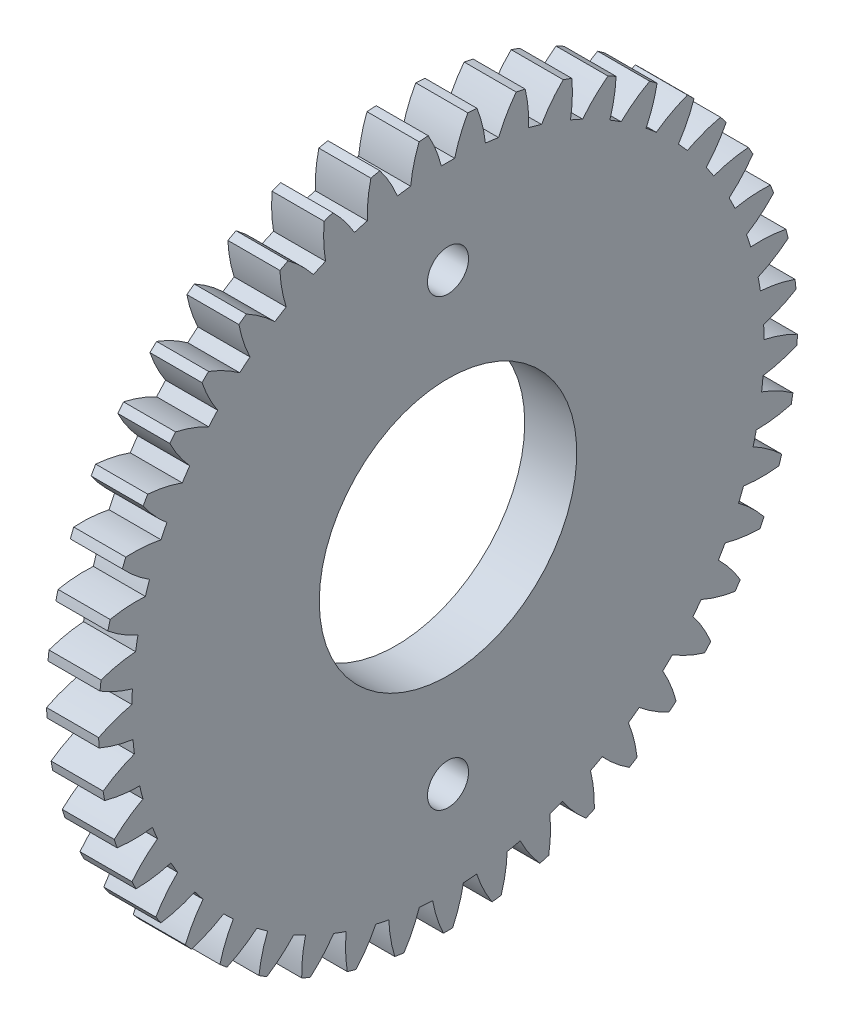
SolidWorks part; units mm, degrees
material "Cedar"
ref_plane "Plane1" through (0, 0, 0) normal (0, 0, 1) x (1, 0, 0)
ref_plane "Plane2" through (0, 0, 0) normal (0, 1, 0) x (1, 0, 0)
ref_plane "Plane3" through (0, 0, 0) normal (1, 0, 0) x (0, 0, -1)
sketch "HoldingSke" plane through (0, 0, 0) normal (0, 1, 0) x (1, 0, 0)
  line L0 (0, 0) -> (359.2102, -359.2102)
  line L1 (-15, 0) -> (100, 0) construction
  line L2 (0, 0) -> (-2.1039, 2.3779)
  line L3 (0, 0) -> (-11.863, 4.5341)
  line L4 (0, 0) -> (6.1066, 6.1066)
  line L5 (0, 0) -> (-47.5972, -17.7524)
  line L6 (0, 0) -> (-3.6847, -2.4861)
  line L7 (-2.1039, 2.3779) -> (8.8308, 51.9871)
  line L8 (-76.2, 54.61) -> (-69.596, 54.61)
  line L9 (-71.009, 38.7566) -> (-53.1078, 45.2721)
  line L10 (-76.2, 71.12) -> (104.1128, 71.12)
  line L11 (0, 0) -> (-4.445, 0)
  line L12 (-76.2, 101.6) -> (-76.1492, 101.6)
  line L13 (24.9733, 27.94) -> (52.9518, 28.4284)
  line L14 (24.9733, 27.94) -> (25.0241, 27.9398)
  line L15 (24.9733, 27.94) -> (100.4021, 29.52)
  circle A0 centre (0, 0) radius 3.175
  circle A1 centre (0, 0) radius 27.0002
  circle A2 centre (0, 0) radius 38.1
  circle A3 centre (0, 0) radius 3.175
  dimension "MHD" = 54.0004
  dimension "Hub_dia" = 76.2
  dimension "Bore" = 6.35
  dimension "MBD" = 6.35
  dimension "Num_teeth" = 45
  dimension "Pitch_radius" = 180.3128
  dimension "Pitch" = 508
  dimension "Width" = 4.445
  dimension "Overall_len" = 50.8
  dimension "Show_teeth" = 45
  dimension "Thickness" = 4.445
  dimension "OAL" = 50.8001
  dimension "T_dim" = 6.604
  dimension "Ap" = 20
  dimension "H" = 19.05
  dimension "Backlash" = 0.0508
  dimension "Addendum_fac" = 1
  dimension "Dedendum_fac" = 1.2
  dimension "Clearance_fac" = 0.2
  dimension "Dedendum_add" = 0.0508
sketch "BasProSke" plane through (0, 0, 0) normal (0, 1, 0) x (1, 0, 0)
  line L0 (-10, 0) -> (60, 0) construction
  line L1 (0, 0) -> (0, 29.845)
  line L2 (0, 0) -> (4.445, 0)
  line L3 (4.445, 0) -> (4.445, 29.845)
  line L4 (4.445, 29.845) -> (0, 29.845)
  dimension "Diameter" = 59.69
  dimension "Thickness" = 4.445
revolve "Base-Revolve" add sketch "BasProSke" angle 360 about L0
sketch "TooCutSke" plane through (0, 0, 0) normal (1, 0, 0) x (0, 0, -1)
  line L1 (0, 0) -> (0, 107) construction
  line L2 (0, 0) -> (-1.0861, 28.5544) construction
  line L3 (0, 0) -> (-3.9846, 56.982) construction
  line L4 (-1.0861, 28.5544) -> (-1.9923, 28.491) construction
  arc A0 (0.5698, 26.9942) -> (-0.5698, 26.9942) centre (0, 0) ccw
  arc A1 (1.7035, 29.8218) -> (-1.7035, 29.8218) centre (0, 0) ccw
  circle A2 centre (0, 0) radius 28.575 construction
  circle A3 centre (0, 0) radius 26.8517 construction
  arc A4 (-0.5698, 26.9942) -> (-1.7035, 29.8218) centre (-11.6511, 24.1923) ccw
  arc A5 (1.7035, 29.8218) -> (0.5698, 26.9942) centre (11.6511, 24.1923) ccw
  dimension "Root_dia" = 54.0004
  dimension "Overcut_dia" = 59.7408
  dimension "Pitch_dia" = 57.15
  dimension "Base_dia" = 53.7034
  dimension "Flank_rad" = 11.43
  dimension "Half_ang" = 4
  dimension "Half_CT" = 0.9084
extrude "ToothCut" cut sketch "TooCutSke" along normal through all
fillet "Breaks" [suppressed] radius 0.0254
fillet "RootFillets" [suppressed] radius 0.3048
pattern_circular "TeethCuts" count 45 over 360 about axis through (0, 0, 0) along (1, 0, 0) of "ToothCut", "RootFillets", "Breaks"
sketch "HubNeaOneSke" plane through (0, 0, 0) normal (-1, 0, 0) x (0, 0, 1)
  circle A0 centre (0, 0) radius 27.0002
  dimension "Diameter" = 54.0004
extrude "HubNearOne" [suppressed] add sketch "HubNeaOneSke" along normal blind 46.3551
sketch "HubNeaBotSke" plane through (0, 0, 0) normal (-1, 0, 0) x (0, 0, 1)
  circle A0 centre (0, 0) radius 27.0002
  dimension "Diameter" = 54.0004
extrude "HubNearBoth" [suppressed] add sketch "HubNeaBotSke" along normal blind 23.1775
ref_plane "FarPln" through (4.445, 0, 0) normal (1, 0, 0) x (0, 0, -1)
sketch "HubFarSke" plane through (4.445, 0, 0) normal (1, 0, 0) x (0, 0, -1)
  circle A0 centre (0, 0) radius 27.0002
  dimension "Diameter" = 54.0004
extrude "HubFar" [suppressed] add sketch "HubFarSke" along normal blind 23.1775
sketch "BorSke" plane through (0, 0, 0) normal (1, 0, 0) x (0, 0, -1)
  circle A0 centre (0, 0) radius 10.9982
  dimension "Diameter" = 21.9964
extrude "Bore" cut sketch "BorSke" along normal mid plane 101.6001
sketch "KeySke" plane through (0, 0, 0) normal (1, 0, 0) x (0, 0, -1)
  line L0 (-0.127, 0) -> (-0.127, 3.429)
  line L1 (-0.127, 3.429) -> (0.127, 3.429)
  line L2 (0.127, 3.429) -> (0.127, 0)
  line L3 (0, 0) -> (0, 34) construction
  line L4 (-0.127, 0) -> (0.127, 0)
  dimension "Offset" = 3.429
  dimension "Width" = 0.254
extrude "Keyway" [suppressed] cut sketch "KeySke" along normal mid plane 101.6001
pattern_circular "Keyway2" [suppressed] count 2 every 90 about axis through (-10, 0, 0) along (1, 0, 0)
sketch "Sketch1" plane through (0, 0, 0) normal (-1, 0, 0) x (0, 0, 1)
  circle A0 centre (0, 18.9992) radius 1.7526
  circle A1 centre (0, -18.9992) radius 1.7526
  point P2 (0, 0)
  dimension "D1" = 3.5052
  dimension "D3" = 3.5052
  dimension "D2" = 18.9992
  dimension "D4" = 18.9992
extrude "Cut-Extrude1" cut sketch "Sketch1" against normal through all
equation "' \"Pitch@HoldingSke\" = 4"
equation "' \"Num_teeth@HoldingSke\" = 12"
equation "' \"Ap@HoldingSke\" =  20"
equation "' \"Width@HoldingSke\" = 0.5"
equation "' \"Hub_dia@HoldingSke\"= 1"
equation "' \"Overall_len@HoldingSke\" = 1.0"
equation "' \"Bore@HoldingSke\" = 0.75"
equation "' \"T_dim@HoldingSke\" = 0.85"
equation "' \"Width@KeySke\" = 0.25"
equation "' \"Show_teeth@HoldingSke\" = 13"
equation "' \"Backlash@HoldingSke\" = 0.009"
equation "' \"Addendum_fac@HoldingSke\" = 1.0"
equation "' \"Dedendum_fac@HoldingSke\" = 1.25"
equation "' \"Dedendum_add@HoldingSke\" = 0.00005"
equation "' \"Clearance_fac@HoldingSke\" = 0.25"
equation "' \"Pitch@HoldingSke\" = 0.5"
equation "' \"Num_teeth@HoldingSke\" = 23"
equation "' \"Show_teeth@HoldingSke\" = 23"
equation "' \"Backlash@HoldingSke\" = 0.0375"
equation "\"Overcut_dia@TooCutSke\" = (\"Num_teeth@HoldingSke\" + 2 * \"Addendum_fac@HoldingSke\") / \"Pitch@HoldingSke\" + 0.002"
equation "\"Pitch_dia@TooCutSke\" = \"Num_teeth@HoldingSke\" / \"Pitch@HoldingSke\""
equation "\"Base_dia@TooCutSke\" = \"Num_teeth@HoldingSke\" / \"Pitch@HoldingSke\" * cos((\"Ap@HoldingSke\"  * 3.14159265 / 180))"
equation "\"Root_dia@TooCutSke\" = (\"Num_teeth@HoldingSke\" + 2) / \"Pitch@HoldingSke\" - 2 * (\"Addendum_fac@HoldingSke\" + \"Dedendum_fac@HoldingSke\") / \"Pitch@HoldingSke\" - \"Dedendum_add@HoldingSke\" * 2"
equation "\"Half_ang@TooCutSke\" = 180 / \"Num_teeth@HoldingSke\""
equation "\"Half_CT@TooCutSke\" = \"Num_teeth@HoldingSke\" / \"Pitch@HoldingSke\" * sin((3.14159265 / 2 / \"Num_teeth@HoldingSke\")) / 2 - 7 * \"Backlash@HoldingSke\" / 4"
equation "\"Flank_rad@TooCutSke\" = \"Num_teeth@HoldingSke\" / \"Pitch@HoldingSke\" / 5"
equation "\"Radius@RootFillets\" = \"Clearance_fac@HoldingSke\" / \"Pitch@HoldingSke\" + \"Dedendum_add@HoldingSke\""
equation "\"Break_rad@Breaks\" = 0.02 / \"Pitch@HoldingSke\""
equation "\"Thickness@HoldingSke\" = \"Width@HoldingSke\""
equation "\"OAL@HoldingSke\" = \"Thickness@HoldingSke\""
equation "\"MHD@HoldingSke\" = (\"Num_teeth@HoldingSke\" + 2) / \"Pitch@HoldingSke\" - 2 * (\"Addendum_fac@HoldingSke\" + \"Dedendum_fac@HoldingSke\")  / \"Pitch@HoldingSke\" - \"Dedendum_add@HoldingSke\" * 2"
equation "\"MBD@HoldingSke\" = (\"Num_teeth@HoldingSke\" + 2) / \"Pitch@HoldingSke\" - 2 * (\"Addendum_fac@HoldingSke\" + \"Dedendum_fac@HoldingSke\")  / \"Pitch@HoldingSke\" - \"Dedendum_add@HoldingSke\" * 2 - 0.002"
equation "\"MHD@HoldingSke\" = ((sgn( \"MHD@HoldingSke\" - \"Hub_dia@HoldingSke\" )-1)*( \"MHD@HoldingSke\" - \"Hub_dia@HoldingSke\" ))/-2+ \"Hub_dia@HoldingSke\""
equation "\"MBD@HoldingSke\" = ((sgn( \"MBD@HoldingSke\" - \"Bore@HoldingSke\" )-1)*( \"MBD@HoldingSke\" - \"Bore@HoldingSke\" ))/-2+ \"Bore@HoldingSke\""
equation "\"OAL@HoldingSke\" = ((sgn( \"OAL@HoldingSke\" - \"Overall_len@HoldingSke\" )+1)*( \"OAL@HoldingSke\" - \"Overall_len@HoldingSke\" ))/2 + \"Overall_len@HoldingSke\" + 0.000002"
equation "\"Num_teeth@TeethCuts\" = int( \"Show_teeth@HoldingSke\" ) + 1"
equation "\"Num_teeth@TeethCuts\" = ((sgn( \"Num_teeth@TeethCuts\" - \"Num_teeth@HoldingSke\" )-1)*( \"Num_teeth@TeethCuts\" - \"Num_teeth@HoldingSke\" ))/-2+ \"Num_teeth@HoldingSke\""
equation "\"Num_teeth@TeethCuts\" = ((sgn( \"Num_teeth@TeethCuts\" - 2.0)+1)*( \"Num_teeth@TeethCuts\" - 2.0))/2 +2.0"
equation "\"Angle@TeethCuts\" = 360.0 / \"Num_teeth@HoldingSke\""
equation "\"Diameter@BasProSke\" = (\"Num_teeth@HoldingSke\" + 2 * \"Addendum_fac@HoldingSke\") / \"Pitch@HoldingSke\""
equation "\"Thickness@BasProSke\"  = \"Thickness@HoldingSke\""
equation "' \"Fillet_rad@BasProSke\" =  \"Thickness@HoldingSke\" * 0.05"
equation "\"MHD@HoldingSke\" = ((sgn( \"MHD@HoldingSke\" - \"Root_dia@TooCutSke\" )-1)*( \"MHD@HoldingSke\" - \"Root_dia@TooCutSke\" ))/-2+ \"Root_dia@TooCutSke\""
equation "\"Diameter@HubNeaOneSke\" = \"MHD@HoldingSke\""
equation "\"Length@HubNearOne\" = \"OAL@HoldingSke\" - \"Thickness@BasProSke\""
equation "\"Diameter@HubNeaBotSke\" = \"MHD@HoldingSke\""
equation "\"Length@HubNearBoth\" = ( \"OAL@HoldingSke\" - \"Thickness@BasProSke\" ) / 2.0"
equation "\"Thickness@FarPln\" = \"Thickness@BasProSke\""
equation "\"Diameter@HubFarSke\" = \"MHD@HoldingSke\""
equation "\"Length@HubFar\" = ( \"OAL@HoldingSke\" - \"Thickness@BasProSke\" ) / 2.0"
equation "\"D1@Bore\" = \"OAL@HoldingSke\" * 2.0"
equation "\"D1@Keyway\" = \"OAL@HoldingSke\" * 2.0"
equation "\"Offset@KeySke\" = \"T_dim@HoldingSke\" - \"MBD@HoldingSke\" / 2.0"
